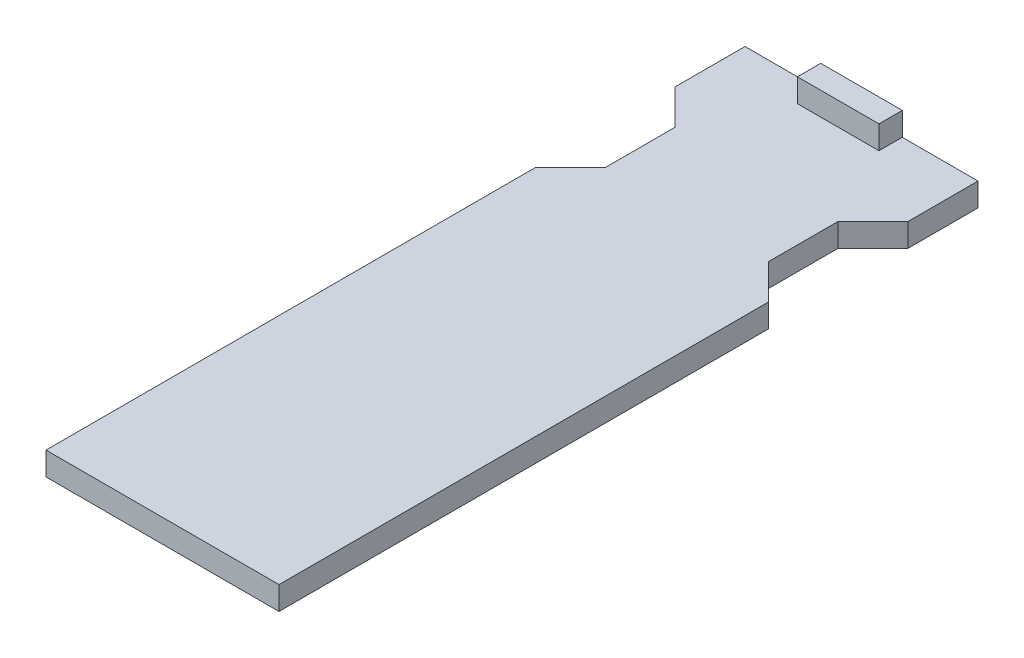
SolidWorks part; units mm, degrees
ref_plane "Front Plane" through (0, 0, 0) normal (0, 0, 1) x (1, 0, 0)
ref_plane "Top Plane" through (0, 0, 0) normal (0, 1, 0) x (1, 0, 0)
ref_plane "Right Plane" through (0, 0, 0) normal (1, 0, 0) x (0, 0, -1)
sketch "Sketch1" plane through (0, 0, 0) normal (0, 1, 0) x (1, 0, 0)
  line L0 (36.2228, 108.6683) -> (173.4812, 108.6683) construction
  line L1 (0, 60) -> (0, 54)
  line L2 (0, 54) -> (3, 51)
  line L3 (3, 51) -> (3, 45)
  line L4 (3, 45) -> (0, 42)
  line L5 (0, 42) -> (0, 0)
  line L6 (0, 0) -> (20, 0)
  line L7 (20, 0) -> (20, 42)
  line L8 (20, 42) -> (17, 45)
  line L9 (17, 45) -> (17, 51)
  line L10 (17, 51) -> (20, 54)
  line L11 (20, 54) -> (20, 60)
  line L12 (20, 60) -> (0, 60)
  dimension "D1" = 60
  dimension "D2" = 20
  dimension "D3" = 14
  dimension "D4" = 6
  dimension "D5" = 6
extrude "Boss-Extrude1" add sketch "Sketch1" along normal blind 2 contours L7 L8 L9 L10 L11 L12 L1 L2 L3 L4 L5 L6
sketch "Sketch2" plane through (0, 2, 0) normal (0, 1, 0) x (1, 0, 0)
  line L0 (20, 60) -> (0, 60) construction
  line L1 (6.5, 60) -> (13.5, 60)
  line L2 (6.5, 60) -> (6.5, 58)
  line L3 (6.5, 58) -> (13.5, 58)
  line L4 (13.5, 60) -> (13.5, 58)
  point P6 (10, 60)
  point P7 (10, 60)
  dimension "D1" = 2
  dimension "D2" = 7
extrude "Boss-Extrude2" add sketch "Sketch2" along normal blind 2 separate body
